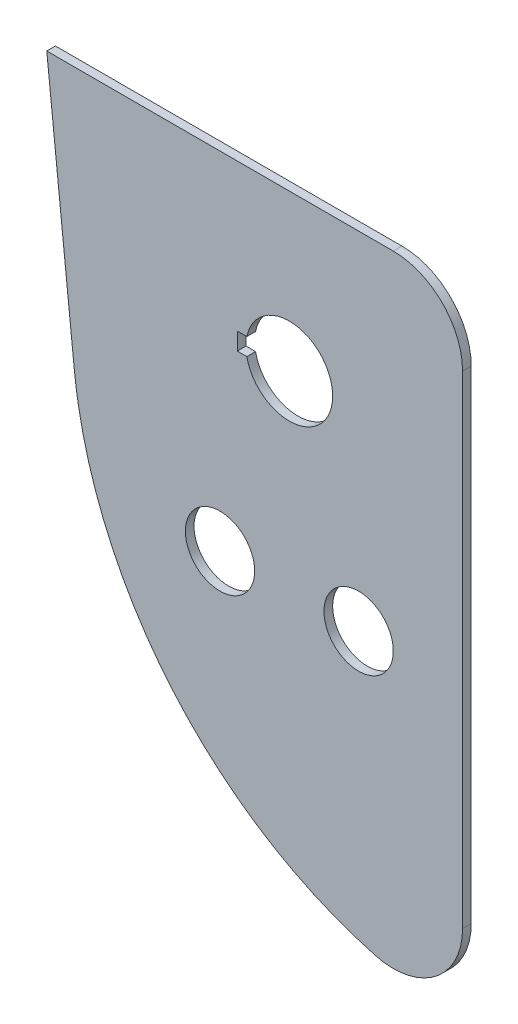
SolidWorks part; units mm, degrees
material "ASTM A36 Steel"
ref_plane "X-Y Datum" through (0, 0, 0) normal (0, 0, 1) x (1, 0, 0)
ref_plane "X-Z Datum" through (0, 0, 0) normal (0, 1, 0) x (1, 0, 0)
ref_plane "Y-Z Datum" through (0, 0, 0) normal (1, 0, 0) x (0, 0, -1)
sketch "Sketch1" plane through (0, 0, 0) normal (0, 0, 1) x (1, 0, 0)
  line L0 (-123.8135, -39.7702) -> (-124.5068, -39.7702)
  line L1 (95.4384, -178.4615) -> (-56.328, -154.9025)
  line L10 (-132.424, 190.9765) -> (-145.9943, 61.7926)
  line L11 (-132.424, 190.9765) -> (-145.9943, 61.7926)
  line L12 (96.4882, 293.3455) -> (-57.5815, 269.5469)
  line L13 (272.8982, 235.8249) -> (143.2259, 287.9688)
  line L14 (374.2028, 188.6741) -> (276.6908, 234.179)
  line L15 (374.3695, -84.0965) -> (374.2028, 188.6741)
  line L16 (374.3695, -84.0965) -> (276.9178, -129.6544)
  line L17 (273.1923, -131.2796) -> (151.618, -199.3813)
  line L18 (63.4252, -214.7982) -> (-75.2115, -162.8954)
  line L19 (-132.106, -88.9937) -> (-145.9943, 43.2174)
  line L20 (-123.8135, -39.7702) -> (35.942, 52.505)
  line L21 (35.942, 52.505) -> (-132.8098, 149.9765)
  line L22 (-134.582, -23.9666) -> (-2.8927, 52.505)
  line L23 (-2.8927, 52.505) -> (-142.3821, 133.5061)
  line L25 (-119.475, -87.6714) -> (-133.3638, 44.5442)
  line L26 (-48.3068, -156.1476) -> (-48.3068, 3.8426)
  line L27 (-123.8135, -39.7702) -> (-48.3068, -39.7702)
  line L28 (67.878, -202.9044) -> (-70.7318, -151.0117) construction
  arc A7 (-57.5815, 269.5469) -> (-132.424, 190.9765) centre (-44.0104, 181.6889) ccw
  arc A8 (143.2259, 287.9688) -> (96.4882, 293.3455) centre (110.0592, 205.4875) ccw
  arc A9 (276.6908, 234.179) -> (272.8982, 235.8249) centre (244.4697, 165.1272) ccw
  arc A10 (273.1923, -131.2796) -> (276.9178, -129.6544) centre (244.4908, -60.4016) ccw
  arc A11 (63.4252, -214.7982) -> (151.618, -199.3813) centre (91.7045, -116.6078) ccw
  arc A12 (-132.106, -88.9937) -> (-75.2115, -162.8954) centre (-43.6746, -79.7649) ccw
  arc A13 (-145.9943, 61.7926) -> (-145.9943, 43.2174) centre (-57.5808, 52.505) ccw
  arc A15 (-119.475, -87.6714) -> (-70.7318, -151.0117) centre (-43.6746, -79.7649) ccw construction
  ellipse E2 centre (-137.596, 141.7413) end of major axis (-133.6394, 148.5491) minor radius 4.7108
  ellipse E4 centre (-137.596, 141.7413) end of major axis (-142.3821, 133.5061) minor radius 5.6986
  ellipse E7 centre (-137.596, -36.7313) end of major axis (-141.5525, -29.9235) minor radius 4.7108
  ellipse E9 centre (-129.1978, -31.8684) end of major axis (-123.8135, -39.7702) minor radius 5.6986
  spline S1 degree 3 poles (-56.328, -154.9025) (-56.3465, -154.8996) (-56.4029, -154.8908) (-56.6111, -154.8582) (-57.1041, -154.7789) (-58.0509, -154.6175) (-60.3544, -154.1857) (-63.3889, -153.4856) (-67.011, -152.4445) (-70.2191, -151.3629) (-73.4464, -150.1038) (-76.613, -148.6946) (-79.7122, -147.1381) (-82.7374, -145.4378) (-85.6822, -143.5974) (-88.5403, -141.6208) (-91.3056, -139.5121) (-93.9722, -137.2761) (-96.5346, -134.9173) (-98.9872, -132.4409) (-101.3249, -129.8521) (-103.5427, -127.1565) (-105.636, -124.3599) (-107.6002, -121.4681) (-109.4314, -118.4874) (-111.1254, -115.424) (-112.6789, -112.2846) (-114.0885, -109.0757) (-115.3513, -105.8042) (-116.4645, -102.477) (-117.4259, -99.1013) (-118.2334, -95.6841) (-118.8853, -92.2327) (-119.2427, -89.7207) (-119.4083, -88.286) (-119.4425, -87.9757) (-119.4592, -87.8204) (-119.4686, -87.7319) (-119.4738, -87.6822) (-119.475, -87.6714) knots 0 0 0 0 0.000571 0.001745 0.00644 0.015831 0.031092 0.078043 0.110904 0.146109 0.181308 0.216502 0.25169 0.286872 0.322047 0.357215 0.392376 0.42753 0.462676 0.497816 0.532948 0.568074 0.603192 0.638304 0.67341 0.708511 0.743605 0.778695 0.81378 0.84886 0.883937 0.919011 0.954083 0.989152 0.994997 0.997335 0.998503 0.999672 1 1 1 1
  point P47 (-124.5068, -39.7702)
  dimension "D2" = 76.2
  dimension "D1" = 12.7
extrude "Boss-Extrude1" add sketch "Sketch1" along normal blind 1.5875
sketch "Sketch2" plane through (0, 0, 0) normal (0, 0, -1) x (-1, 0, 0)
  line L1 (80.0568, -39.7702) -> (80.0568, -146.9231) construction
  line L2 (124.5068, -39.7702) -> (48.3068, -39.7702) construction
  line L3 (67.3568, -103.2702) -> (92.7568, -103.2702) construction
  line L4 (124.5068, -39.7702) -> (48.3068, -39.7702) construction
  line L9 (89.5818, -66.7577) -> (86.4068, -66.7577)
  line L10 (89.5818, -66.7577) -> (89.5818, -69.9327)
  line L11 (89.5818, -69.9327) -> (86.4068, -69.9327)
  line L12 (86.4068, -66.7577) -> (86.4068, -69.9327)
  line L13 (89.5818, -66.7577) -> (86.4068, -69.9327) construction
  line L14 (89.5818, -69.9327) -> (86.4068, -66.7577) construction
  circle A1 centre (67.3568, -103.2702) radius 6.35
  circle A2 centre (80.0568, -68.3452) radius 7.9375
  circle A3 centre (92.7568, -103.2702) radius 6.35
  circle A4 centre (80.0568, -68.3452) radius 15.875 construction
  spline S0 degree 3 poles (56.328, -154.9025) (56.3465, -154.8996) (56.4029, -154.8908) (56.6111, -154.8582) (57.1041, -154.7789) (58.0509, -154.6175) (60.3544, -154.1857) (63.3889, -153.4856) (67.011, -152.4445) (70.2191, -151.3629) (73.4464, -150.1038) (76.613, -148.6946) (79.7122, -147.1381) (82.7374, -145.4378) (85.6822, -143.5974) (88.5403, -141.6208) (91.3056, -139.5121) (93.9722, -137.2761) (96.5346, -134.9173) (98.9872, -132.4409) (101.3249, -129.8521) (103.5427, -127.1565) (105.636, -124.3599) (107.6002, -121.4681) (109.4314, -118.4874) (111.1254, -115.424) (112.6789, -112.2846) (114.0885, -109.0757) (115.3513, -105.8042) (116.4645, -102.477) (117.4259, -99.1013) (118.2334, -95.6841) (118.8853, -92.2327) (119.2427, -89.7207) (119.4083, -88.286) (119.4425, -87.9757) (119.4592, -87.8204) (119.4686, -87.7319) (119.4738, -87.6822) (119.475, -87.6714) knots 0 0 0 0 0.000571 0.001745 0.00644 0.015831 0.031092 0.078043 0.110904 0.146109 0.181308 0.216502 0.25169 0.286872 0.322047 0.357215 0.392376 0.42753 0.462676 0.497816 0.532948 0.568074 0.603192 0.638304 0.67341 0.708511 0.743605 0.778695 0.81378 0.84886 0.883937 0.919011 0.954083 0.989152 0.994997 0.997335 0.998503 0.999672 1 1 1 1 construction
  point P1 (80.0568, -103.2702)
  point P8 (87.9943, -68.3452)
  point P15 (87.9943, -68.3452)
  point P16 (73.7068, -103.2702)
  point P17 (86.4068, -103.2702)
  point P26 (86.4068, -39.7702)
  dimension "D1" = 15.875
  dimension "D2" = 31.75
  dimension "D3" = 12.7
  dimension "D4" = 34.925
  dimension "D5" = 25.4
  dimension "D6" = 28.575
  dimension "D7" = 3.175
  dimension "D8" = 3.175
  dimension "D9" = 6.35
extrude "Cut-Extrude1" cut sketch "Sketch2" against normal through all contours A1 | A3 | L9 A2 L11 L12 | A2 L11 L10 L9 | L11 A2 L9 L12
fillet "Fillet1" radius 12.7 2 edges at (-48.3068, -39.7702, 0.7937) (-48.3068, -156.1476, 0.7937)
